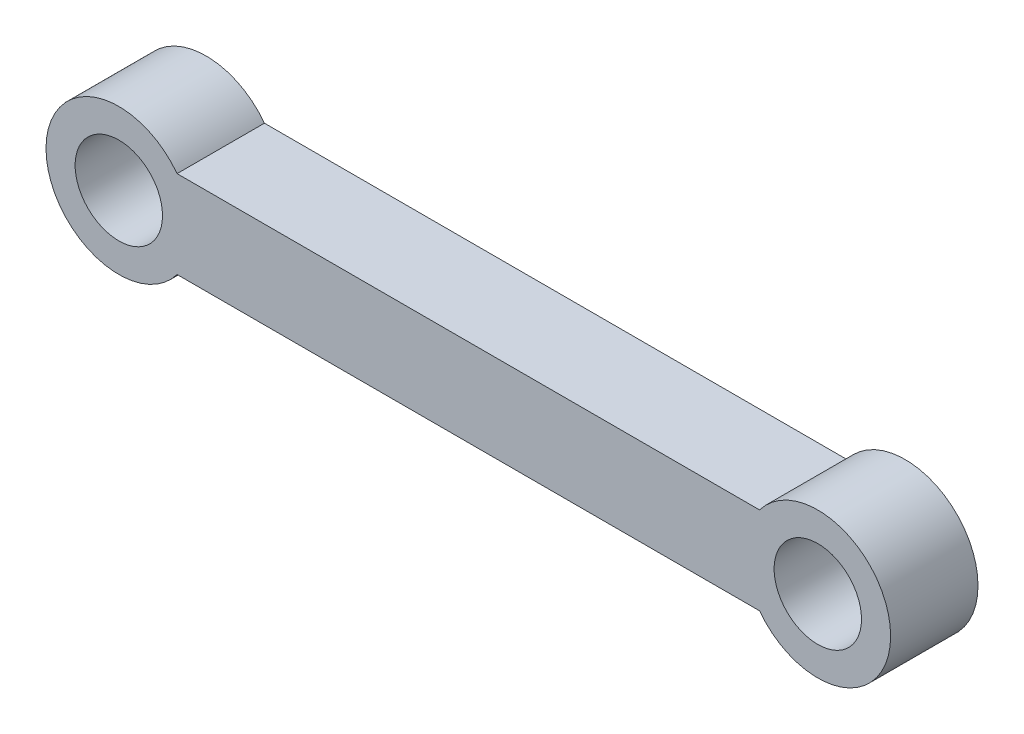
SolidWorks part; units mm, degrees
ref_plane "前视基准面" through (0, 0, 0) normal (0, 0, 1) x (1, 0, 0)
ref_plane "上视基准面" through (0, 0, 0) normal (0, 1, 0) x (1, 0, 0)
ref_plane "右视基准面" through (0, 0, 0) normal (1, 0, 0) x (0, 0, -1)
other "Configuration Table"
sketch "草图1" plane through (0, 0, 0) normal (0, 0, 1) x (1, 0, 0)
  line L0 (0, 0) -> (47214.7619, 0) construction
  line L1 (0, 0) -> (0, 47214.7619) construction
  line L2 (-24, 3) -> (24, 3)
  line L3 (-30, 5) -> (30, 5)
  line L4 (-30, 5) -> (-30, -5)
  line L5 (-30, -5) -> (30, -5)
  line L6 (30, 5) -> (30, -5)
  line L7 (-24, -3) -> (24, -3)
  circle A0 centre (-24, 0) radius 3
  circle A1 centre (24, 0) radius 3
  circle A2 centre (-24, 0) radius 5
  circle A3 centre (24, 0) radius 5
  dimension "D1" = 6
  dimension "D2" = 6
extrude "凸台-拉伸1" add sketch "草图1" along normal blind 6 contours A3 L2 A2 L7 | L2 A2 L7 A0 | A3 L2 A1 L7 | L2 A3 L7 A1 | L7 A2 L2 A0
